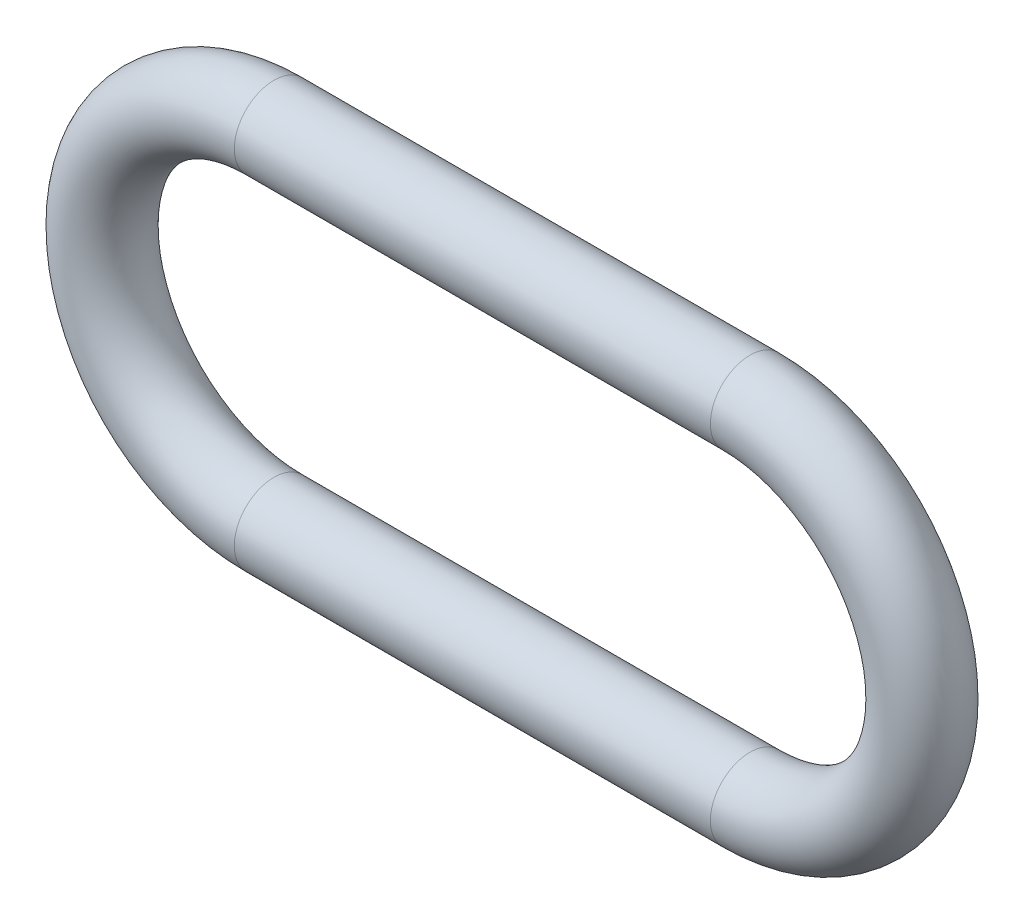
SolidWorks part; units mm, degrees
ref_plane "Plan de face" through (0, 0, 0) normal (0, 0, 1) x (1, 0, 0)
ref_plane "Plan de dessus" through (0, 0, 0) normal (0, 1, 0) x (1, 0, 0)
ref_plane "Plan de droite" through (0, 0, 0) normal (1, 0, 0) x (0, 0, -1)
sketch "Esquisse1" plane through (0, 0, 0) normal (0, 0, 1) x (1, 0, 0)
  line L0 (0, 6.5) -> (18, 6.5)
  line L1 (18, -6.5) -> (0, -6.5)
  line L2 (0, 6.5) -> (0, -6.5) construction
  line L3 (18, 6.5) -> (18, -6.5) construction
  circle A0 centre (0, 0) radius 5 construction
  circle A1 centre (18, 0) radius 5 construction
  arc A4 (18, 6.5) -> (18, -6.5) centre (18, 0) cw
  arc A5 (0, 6.5) -> (0, -6.5) centre (0, 0) ccw
  point P3 (0, 0)
  dimension "D1" = 10
  dimension "D2" = 10
  dimension "D4" = 1.5
  dimension "D3" = 18
sketch "Esquisse2" plane through (0, 0, 0) normal (1, 0, 0) x (0, 0, -1)
  circle A0 centre (0, 6.5) radius 1.5
  dimension "D1" = 3
sweep "Balayage1" add profiles "Esquisse2" path "Esquisse1"
